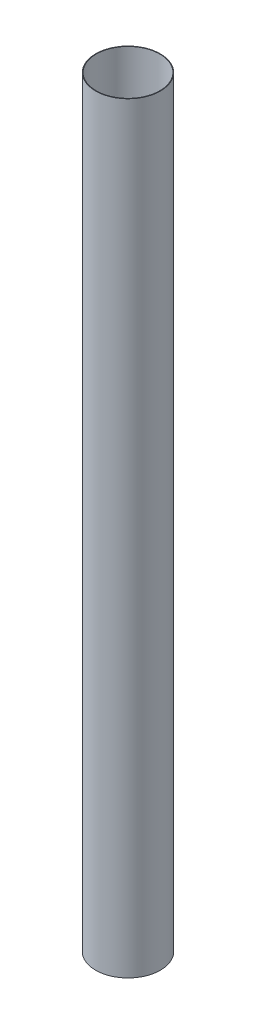
SolidWorks part; units mm, degrees
material "Acrylic (Medium-high impact)"
ref_plane "Front Plane" through (0, 0, 0) normal (0, 0, 1) x (1, 0, 0)
ref_plane "Top Plane" through (0, 0, 0) normal (0, 1, 0) x (1, 0, 0)
ref_plane "Right Plane" through (0, 0, 0) normal (1, 0, 0) x (0, 0, -1)
sketch "Sketch1" plane through (0, 0, 0) normal (0, 1, 0) x (1, 0, 0)
  circle A0 centre (0, 0) radius 30.5
  circle A1 centre (0, 0) radius 30
extrude "Boss-Extrude1" add sketch "Sketch1" along normal blind 718
